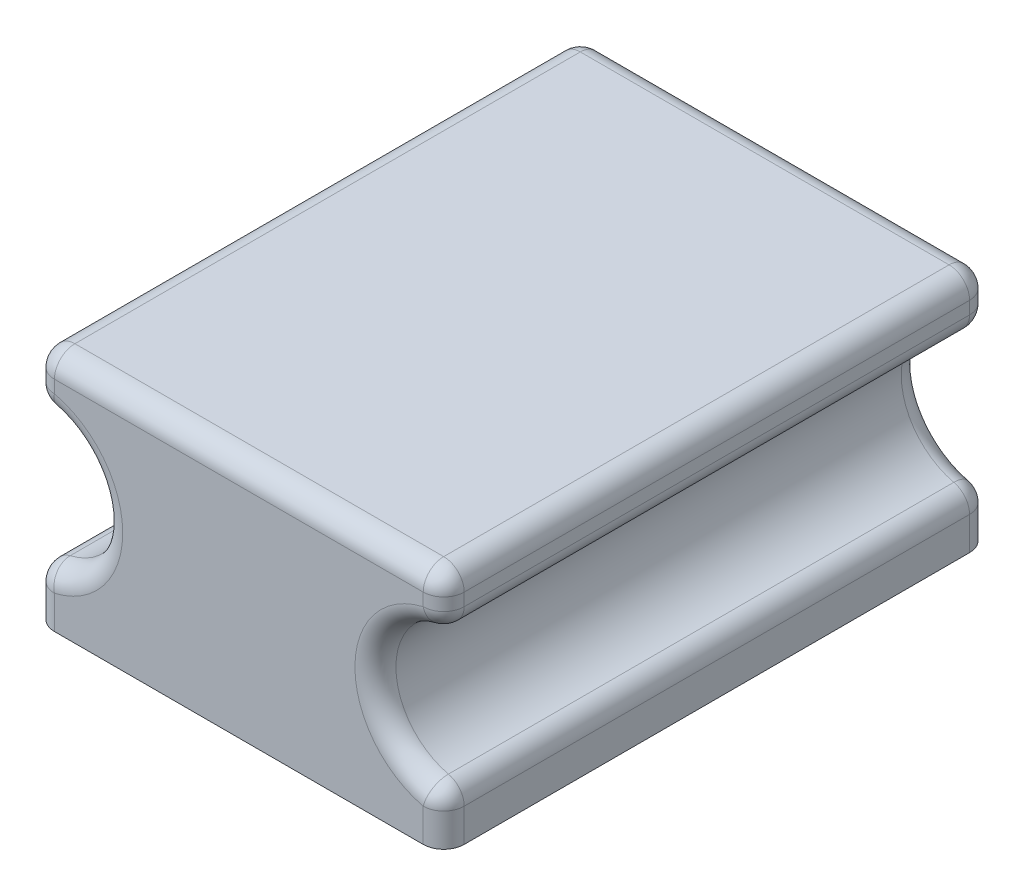
SolidWorks part; units mm, degrees
material "Полиуретановый гибкий пенопласт"
ref_plane "Спереди" through (0, 0, 0) normal (0, 0, 1) x (1, 0, 0)
ref_plane "Сверху" through (0, 0, 0) normal (0, 1, 0) x (1, 0, 0)
ref_plane "Справа" through (0, 0, 0) normal (1, 0, 0) x (0, 0, -1)
sketch "Эскиз1" plane through (0, 0, 0) normal (0, 0, 1) x (1, 0, 0)
  line L0 (-30, 0) -> (30, 0)
  line L1 (30, 0) -> (30, 7.5)
  line L2 (30, 35) -> (-30, 35)
  line L3 (-30, 35) -> (-30, 27.5)
  line L4 (-30, 7.5) -> (-30, 0)
  line L5 (30, 27.5) -> (30, 35)
  line L6 (0, 0) -> (0, 35) construction
  line L7 (-30, 17.5) -> (30, 17.5) construction
  arc A0 (30, 27.5) -> (30, 7.5) centre (30, 17.5) ccw
  arc A1 (-30, 7.5) -> (-30, 27.5) centre (-30, 17.5) ccw
  point P12 (0, 17.5)
  dimension "D1" = 60
  dimension "D2" = 35
  dimension "D3" = 20
extrude "Бобышка-Вытянуть1" add sketch "Эскиз1" along normal mid plane 80
fillet "Скругление1" radius 3 6 edges at (30, 7.5, 0) (-30, 7.5, 0) (-30, 27.5, 0) (30, 27.5, 0) (-30, 35, 0) (30, 35, 0)
fillet "Скругление2" radius 3 26 edges at (30, 2.4254, -40) (29.3534, 6.7114, -40) (20, 17.5, -40) (29.3534, 28.2886, -40) (30, 31.0746, -40) (29.1213, 34.1213, -40) (-30, 2.4254, -40) (-29.3534, 6.7114, -40) (-20, 17.5, -40) (-29.3534, 28.2886, -40) (-30, 31.0746, -40) (-29.1213, 34.1213, -40) (30, 2.4254, 40) (29.3534, 6.7114, 40) (20, 17.5, 40) (29.3534, 28.2886, 40) (30, 31.0746, 40) (29.1213, 34.1213, 40) (-30, 2.4254, 40) (-29.3534, 6.7114, 40) (-20, 17.5, 40) (-29.3534, 28.2886, 40) (-30, 31.0746, 40) (-29.1213, 34.1213, 40) (0, 35, -40) (0, 35, 40)
